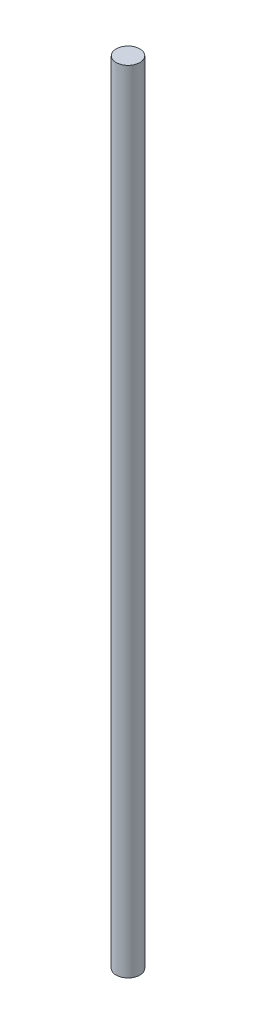
SolidWorks part; units mm, degrees
ref_plane "Front Plane" through (0, 0, 0) normal (0, 0, 1) x (1, 0, 0)
ref_plane "Top Plane" through (0, 0, 0) normal (0, 1, 0) x (1, 0, 0)
ref_plane "Right Plane" through (0, 0, 0) normal (1, 0, 0) x (0, 0, -1)
sketch "Sketch2" plane through (0, 0, 0) normal (0, 1, 0) x (1, 0, 0)
  circle A0 centre (0, 0) radius 6
  dimension "D1" = 12
extrude "Boss-Extrude1" add sketch "Sketch2" along normal blind 400
